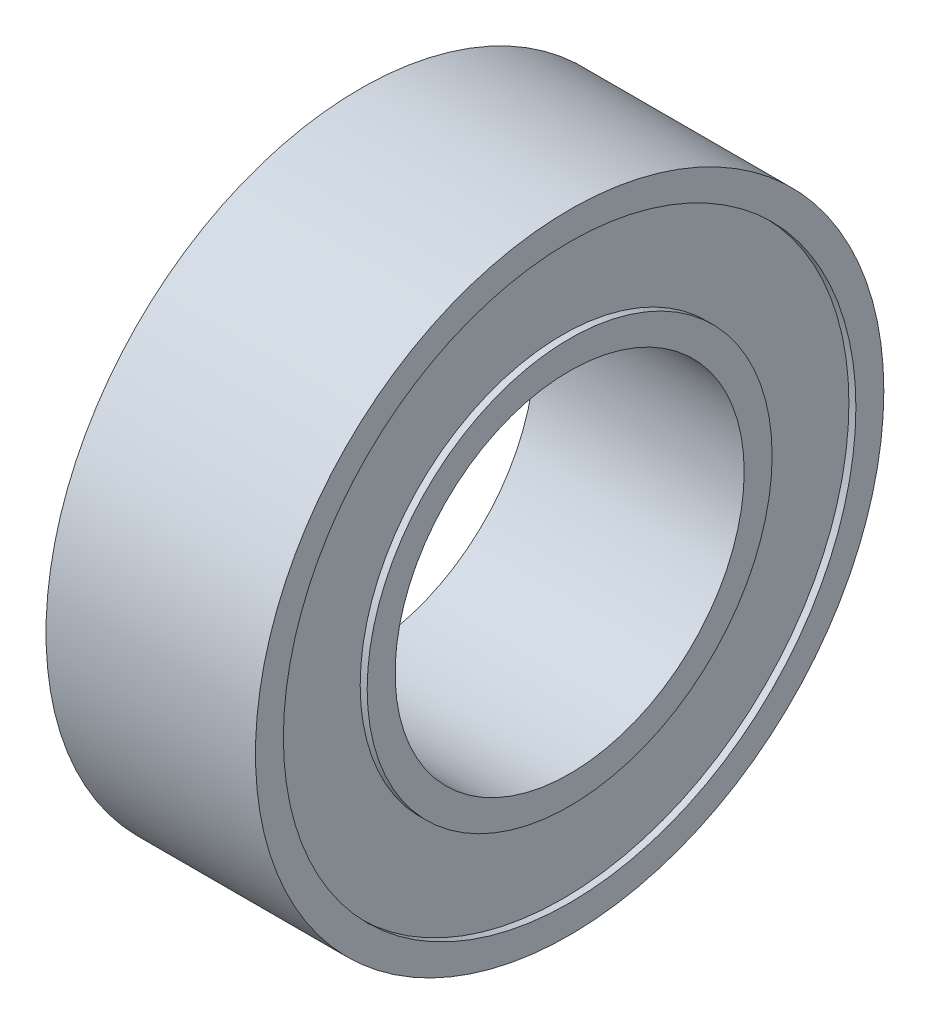
SolidWorks part; units mm, degrees
ref_plane "Front Plane" through (0, 0, 0) normal (0, 0, 1) x (1, 0, 0)
ref_plane "Top Plane" through (0, 0, 0) normal (0, 1, 0) x (1, 0, 0)
ref_plane "Right Plane" through (0, 0, 0) normal (1, 0, 0) x (0, 0, -1)
sketch "Sketch1" plane through (0, 0, 0) normal (1, 0, 0) x (0, 0, -1)
  circle A0 centre (0, 0) radius 4.5
  circle A1 centre (0, 0) radius 2.5
  dimension "D1" = 9
  dimension "D2" = 5
extrude "Boss-Extrude1" add sketch "Sketch1" along normal blind 3
sketch "Sketch2" plane through (3, 0, 0) normal (1, 0, 0) x (0, 0, -1)
  circle A0 centre (0, 0) radius 4.1
  circle A1 centre (0, 0) radius 2.9
  circle A2 centre (0, 0) radius 4.5 construction
  circle A3 centre (0, 0) radius 2.5 construction
  dimension "D1" = 0.4
  dimension "D2" = 0.4
extrude "Cut-Extrude1" cut sketch "Sketch2" against normal blind 0.1
sketch "Sketch3" plane through (0, 0, 0) normal (-1, 0, 0) x (0, 0, 1)
  circle A0 centre (0, 0) radius 4.1
  circle A1 centre (0, 0) radius 2.9
  circle A2 centre (0, 0) radius 2.5 construction
  circle A3 centre (0, 0) radius 4.5 construction
  dimension "D1" = 0.4
  dimension "D2" = 0.4
extrude "Cut-Extrude2" cut sketch "Sketch3" against normal blind 0.1
